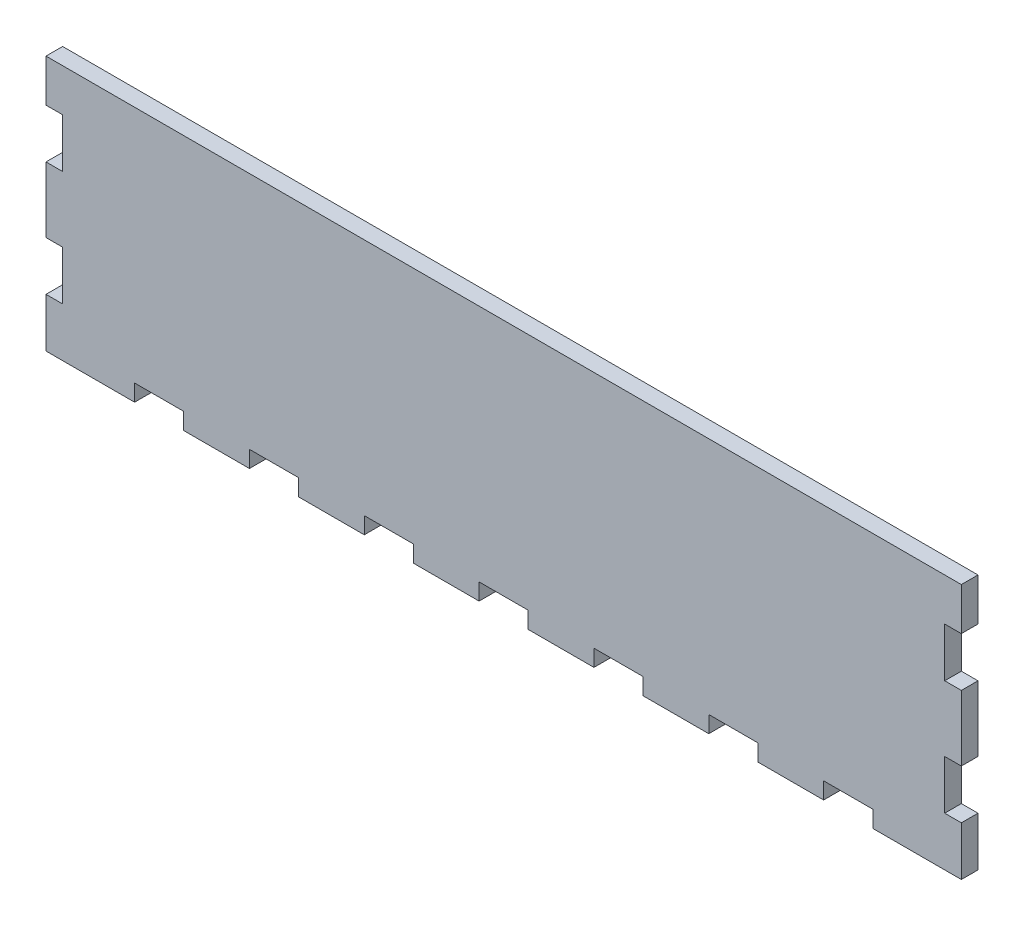
SolidWorks part; units mm, degrees
ref_plane "Front Plane" through (0, 0, 0) normal (0, 0, 1) x (1, 0, 0)
ref_plane "Top Plane" through (0, 0, 0) normal (0, 1, 0) x (1, 0, 0)
ref_plane "Right Plane" through (0, 0, 0) normal (1, 0, 0) x (0, 0, -1)
sketch "Sketch27" plane through (0, 0, 0) normal (0, 0, 1) x (1, 0, 0)
  line L0 (-5.2016, -266.3604) -> (21.8424, -266.3601)
  line L1 (36.8424, -266.3601) -> (56.8944, -266.3601)
  line L2 (-5.2016, -266.3604) -> (-5.2016, -251.3604)
  line L3 (-5.2016, -188.3804) -> (274.1984, -188.3804)
  line L4 (274.1984, -266.3604) -> (274.1984, -251.3603)
  line L5 (-5.2016, -201.3604) -> (-5.2016, -188.3804)
  line L6 (-5.2016, -216.3604) -> (-0.1216, -216.3604)
  line L7 (-5.2016, -251.3604) -> (-0.1216, -251.3604)
  line L8 (-5.2016, -236.3604) -> (-5.2016, -216.3604)
  line L9 (-5.2016, -236.3604) -> (-0.1216, -236.3604)
  line L10 (274.1984, -216.3603) -> (269.1184, -216.3603)
  line L11 (-5.2016, -201.3604) -> (-0.1216, -201.3604)
  line L12 (-0.1216, -216.3604) -> (-0.1216, -201.3604)
  line L13 (274.1984, -236.3603) -> (274.1984, -216.3603)
  line L14 (269.1184, -216.3603) -> (269.1184, -201.3603)
  line L15 (274.1984, -251.3603) -> (269.1184, -251.3603)
  line L16 (274.1984, -201.3603) -> (269.1184, -201.3603)
  line L17 (274.1984, -236.3603) -> (269.1184, -236.3603)
  line L18 (-0.1216, -236.3604) -> (-0.1216, -251.3604)
  line L19 (274.1984, -201.3603) -> (274.1984, -188.3804)
  line L20 (269.1184, -236.3603) -> (269.1184, -251.3603)
  line L22 (141.9984, -266.3604) -> (162.0504, -266.3604)
  line L24 (71.8944, -266.3601) -> (91.9464, -266.3601)
  line L25 (106.9464, -266.3601) -> (126.9984, -266.3604)
  line L26 (177.0504, -266.3604) -> (197.1024, -266.3601)
  line L27 (212.1024, -266.3601) -> (232.1544, -266.3601)
  line L28 (247.1544, -266.3601) -> (274.1984, -266.3604)
  line L49 (21.8424, -261.2801) -> (36.8424, -261.2801)
  line L50 (21.8424, -261.2801) -> (21.8424, -266.3601)
  line L52 (36.8424, -261.2801) -> (36.8424, -266.3601)
  line L53 (56.8944, -261.2801) -> (71.8944, -261.2801)
  line L55 (56.8944, -261.2801) -> (56.8944, -266.3601)
  line L56 (71.8944, -261.2801) -> (71.8944, -266.3601)
  line L57 (91.9464, -261.2801) -> (91.9464, -266.3601)
  line L58 (91.9464, -261.2801) -> (106.9464, -261.2801)
  line L60 (106.9464, -261.2801) -> (106.9464, -266.3601)
  line L61 (126.9984, -261.2801) -> (126.9984, -266.3604)
  line L62 (126.9984, -261.2801) -> (141.9984, -261.2801)
  line L64 (141.9984, -261.2801) -> (141.9984, -266.3604)
  line L65 (162.0504, -261.2801) -> (162.0504, -266.3604)
  line L66 (162.0504, -261.2801) -> (177.0504, -261.2801)
  line L68 (177.0504, -261.2801) -> (177.0504, -266.3604)
  line L69 (197.1024, -261.2801) -> (197.1024, -266.3601)
  line L70 (197.1024, -261.2801) -> (212.1024, -261.2801)
  line L72 (212.1024, -261.2801) -> (212.1024, -266.3601)
  line L73 (232.1544, -261.2801) -> (232.1544, -266.3601)
  line L74 (232.1544, -261.2801) -> (247.1544, -261.2801)
  line L76 (247.1544, -261.2801) -> (247.1544, -266.3601)
  dimension "D1" = 279.4
  dimension "D2" = 15
  dimension "D3" = 5.08
  dimension "D4" = 20
  dimension "D5" = 15
  dimension "D6" = 15
  dimension "D7" = 5.08
extrude "Boss-Extrude1" add sketch "Sketch27" along normal blind 5.08
